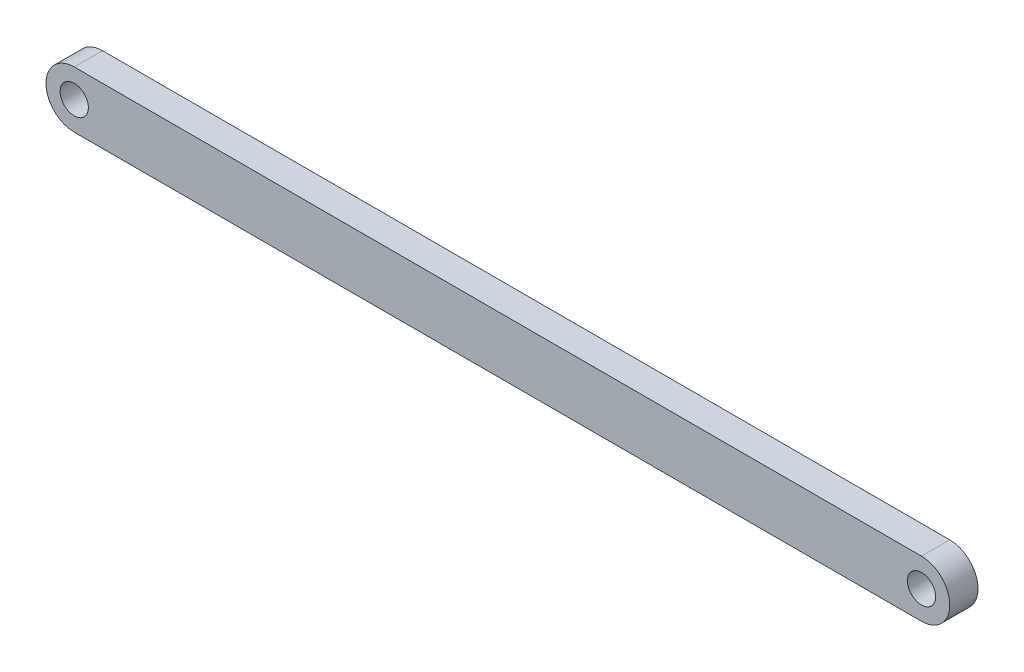
SolidWorks part; units mm, degrees
material "合金鋼"
ref_plane "正面" through (0, 0, 0) normal (0, 0, 1) x (1, 0, 0)
ref_plane "平面" through (0, 0, 0) normal (0, 1, 0) x (1, 0, 0)
ref_plane "右側面" through (0, 0, 0) normal (1, 0, 0) x (0, 0, -1)
sketch "ｽｹｯﾁ1" plane through (0, 0, 0) normal (0, 0, 1) x (1, 0, 0)
  line L1 (-150, -10) -> (150, -10)
  line L2 (-150, -10) -> (-150, 10)
  line L3 (-150, 10) -> (150, 10)
  line L4 (150, -10) -> (150, 10)
  line L5 (-150, -10) -> (150, 10) construction
  line L6 (-150, 10) -> (150, -10) construction
  circle A0 centre (-150, 0) radius 10
  circle A1 centre (150, 0) radius 10
  circle A2 centre (150, 0) radius 5
  circle A3 centre (-150, 0) radius 5
  point P0 (0, 0)
extrude "ﾎﾞｽ - 押し出し1" add sketch "ｽｹｯﾁ1" along normal blind 10 contours A3 L2 A0 | A3 L2 A0 | A1 L3 A0 L1 | A2 L4 A1 | A2 L4 A1
